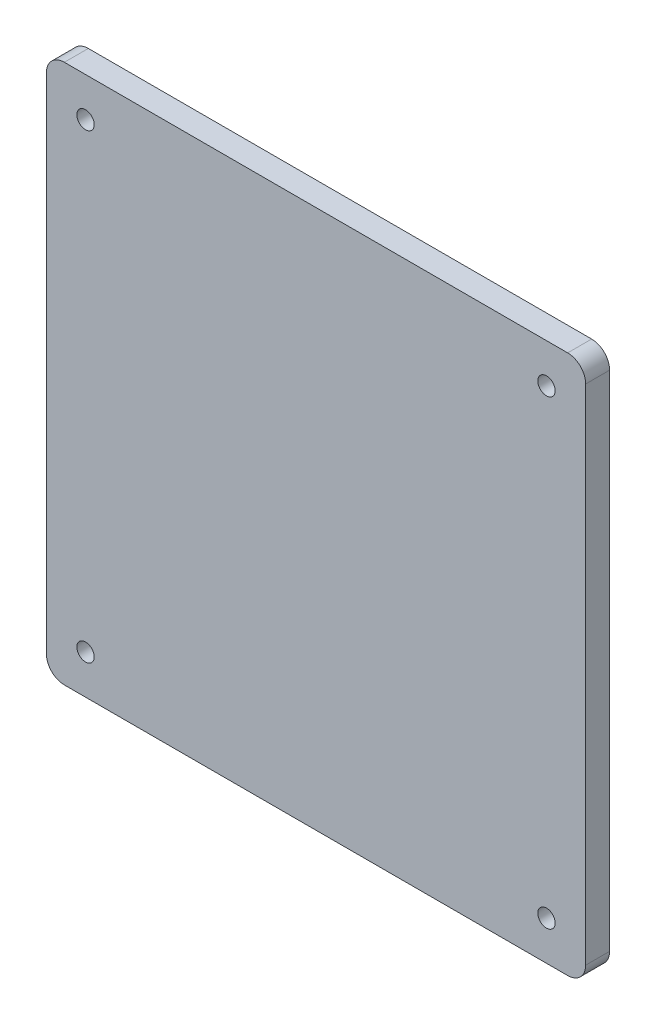
SolidWorks part; units mm, degrees
ref_plane "Front Plane" through (0, 0, 0) normal (0, 0, 1) x (1, 0, 0)
ref_plane "Top Plane" through (0, 0, 0) normal (0, 1, 0) x (1, 0, 0)
ref_plane "Right Plane" through (0, 0, 0) normal (1, 0, 0) x (0, 0, -1)
sketch "Sketch1" plane through (0, 0, 0) normal (0, 0, 1) x (1, 0, 0)
  line L1 (42, 45) -> (-42, 45)
  line L2 (45, 42) -> (45, -42)
  line L3 (42, -45) -> (-42, -45)
  line L4 (-45, 42) -> (-45, -42)
  line L5 (44.1213, 44.1213) -> (-44.1213, -44.1213) construction
  line L6 (44.1213, -44.1213) -> (-44.1213, 44.1213) construction
  arc A0 (45, 42) -> (42, 45) centre (42, 42) ccw construction
  circle A1 centre (-38.4645, -38.4645) radius 1.45
  circle A2 centre (-38.4645, -38.4645) radius 1.45
  circle A3 centre (38.4645, -38.4645) radius 1.45
  circle A4 centre (38.4645, -38.4645) radius 1.45
  circle A5 centre (38.4645, 38.4645) radius 1.45
  circle A6 centre (38.4645, 38.4645) radius 1.45
  circle A7 centre (-38.4645, 38.4645) radius 1.45
  circle A8 centre (-38.4645, 38.4645) radius 1.45
  arc A9 (42, -45) -> (45, -42) centre (42, -42) ccw construction
  arc A10 (-45, -42) -> (-42, -45) centre (-42, -42) ccw construction
  arc A11 (-42, 45) -> (-45, 42) centre (-42, 42) ccw construction
  arc A12 (45, 42) -> (42, 45) centre (42, 42) ccw
  arc A13 (42, -45) -> (45, -42) centre (42, -42) ccw
  arc A14 (-45, -42) -> (-42, -45) centre (-42, -42) ccw
  arc A15 (-42, 45) -> (-45, 42) centre (-42, 42) ccw
  point P0 (0, 0)
  dimension "D1" = 0
  dimension "D2" = 0
  dimension "D3" = 0
  dimension "D4" = 0
extrude "Boss-Extrude1" add sketch "Sketch1" along normal blind 4
